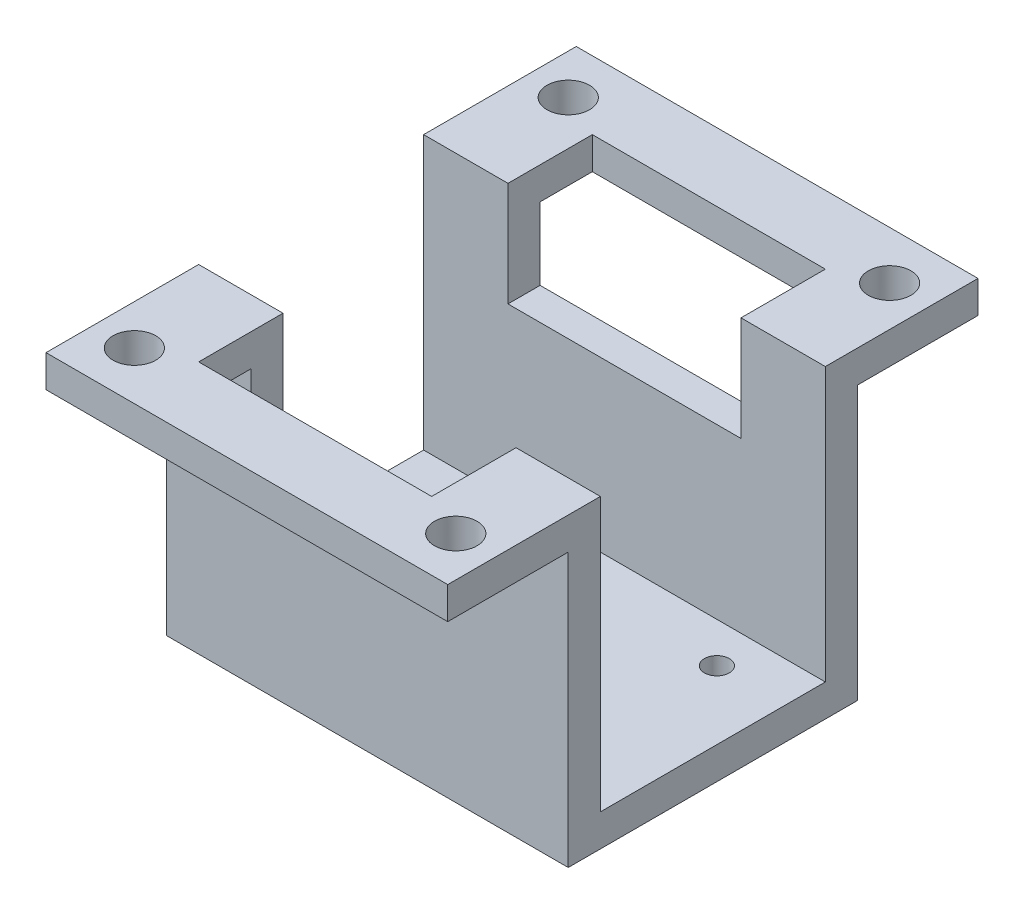
SolidWorks part; units mm, degrees
ref_plane "Front Plane" through (0, 0, 0) normal (0, 0, 1) x (1, 0, 0)
ref_plane "Top Plane" through (0, 0, 0) normal (0, 1, 0) x (1, 0, 0)
ref_plane "Right Plane" through (0, 0, 0) normal (1, 0, 0) x (0, 0, -1)
sketch "Sketch1" plane through (0, 0, 0) normal (0, 1, 0) x (1, 0, 0)
  line L6 (-8.5, 27) -> (41.5, 27)
  line L7 (-8.5, 27) -> (-8.5, -9)
  line L8 (-8.5, -9) -> (41.5, -9)
  line L9 (41.5, 27) -> (41.5, -9)
  circle A0 centre (0, 18) radius 1.55
  circle A1 centre (0, 0) radius 1.55
  circle A2 centre (33, 0) radius 1.55
  circle A3 centre (33, 18) radius 1.55
  circle A4 centre (9, 9) radius 8
  dimension "D3" = 3.1
  dimension "D8" = 16
  dimension "D1" = 33
  dimension "D2" = 18
  dimension "D4" = 50
  dimension "D5" = 36
extrude "Boss-Extrude1" add sketch "Sketch1" along normal blind 4
sketch "Sketch2" plane through (0, 4, 0) normal (0, 1, 0) x (1, 0, 0)
  line L0 (-8.5, -9) -> (41.5, -9)
  line L1 (-8.5, -5) -> (41.5, -5)
  line L2 (-8.5, -5) -> (-8.5, -9)
  line L3 (-8.5, -9) -> (-8.5964, -8.8741)
  line L4 (41.5, -5) -> (41.5, -9)
  line L5 (-8.5, 9) -> (41.5, 9) construction
  line L6 (-8.5, 27) -> (-8.5, -9) construction
  line L7 (41.5, -9) -> (41.5, 27) construction
  line L8 (-8.5, 23) -> (41.5, 23)
  line L9 (41.5, 23) -> (41.5, 27)
  line L10 (-8.5, 23) -> (-8.5, 27)
  line L11 (-8.5, 27) -> (41.5, 27)
  circle A0 centre (0, 0) radius 1.55
  circle A1 centre (0, 0) radius 2.75
  line M3 (41.5, -9) -> (41.5, 27)
  line M4 (41.5, 27) -> (-8.5, 27)
  line M5 (-8.5, 27) -> (-8.5, -9)
  line M6 (-8.5, -9) -> (41.5, -9)
  dimension "D1" = 5.5
  dimension "D2" = 4
extrude "Boss-Extrude3" add sketch "Sketch2" along normal blind 34 contours L1 M5 M6 M3 | L8 M5 M3 M4
sketch "Sketch3" plane through (0, 0, 9) normal (0, 0, 1) x (1, 0, 0)
  line L1 (2, 38) -> (31, 38)
  line L2 (2, 25) -> (31, 25)
  line L5 (2, 38) -> (2, 25)
  line L6 (31, 38) -> (31, 25)
extrude "Cut-Extrude1" cut sketch "Sketch3" against normal through all
sketch "Sketch6" plane through (0, 0, 9) normal (0, 0, 1) x (1, 0, 0)
  line L0 (31, 38) -> (41.5, 38)
  line L1 (-8.5, 38) -> (31, 38)
  line L2 (-8.5, 34) -> (2, 34)
  line L3 (2, 34) -> (41.5, 34)
  line L4 (-8.5, 38) -> (2, 38) construction
  line L5 (31, 34) -> (41.5, 34) construction
  line L6 (-8.5, 38) -> (-8.5, 34)
  line L7 (41.5, 38) -> (41.5, 34)
  dimension "D1" = 4
extrude "Boss-Extrude4" add sketch "Sketch6" along normal blind 15
sketch "Sketch7" plane through (0, 0, -27) normal (0, 0, -1) x (-1, 0, 0)
  line L0 (8.5, 38) -> (-41.5, 38)
  line L1 (8.5, 34) -> (-41.5, 34)
  line L2 (8.5, 38) -> (8.5, 34)
  line L3 (-41.5, 38) -> (-41.5, 34)
  dimension "D1" = 4
extrude "Boss-Extrude5" add sketch "Sketch7" along normal blind 15
sketch "Sketch9" plane through (0, 38, 0) normal (0, 1, 0) x (1, 0, 0)
  line L0 (2, 27) -> (31, 27)
  line L1 (2, -9) -> (31, -9)
  line L2 (2, 33.5) -> (31, 33.5)
  line L3 (2, -15.5) -> (31, -15.5)
  line L4 (2, 27) -> (2, 33.5)
  line L5 (31, 33.5) -> (31, 27)
  line L6 (2, -15.5) -> (2, -9)
  line L7 (31, -9) -> (31, -15.5)
  dimension "D1" = 6.5
  dimension "D2" = 6.5
extrude "Cut-Extrude2" cut sketch "Sketch9" against normal through all
sketch "Sketch10" plane through (0, 34, 0) normal (0, -1, 0) x (1, 0, 0)
  line L0 (41.5, -42) -> (36.5, -42)
  line L1 (16.5, -42) -> (16.5, 24) construction
  line L3 (-8.5, 24) -> (41.5, 24) construction
  line L4 (41.5, -42) -> (41.5, 24)
  line L5 (41.5, -42) -> (-8.5, -42) construction
  line L6 (41.5, -9) -> (-18.2111, -9) construction
  line L11 (36.25, -42) -> (38.9195, -42)
  line L12 (36.5, -42) -> (36.5, -36)
  circle A0 centre (36.5, -36) radius 2.65
  circle A1 centre (-3.5, -36) radius 2.65
  circle A2 centre (-3.5, 18) radius 2.65
  circle A3 centre (36.5, 18) radius 2.65
  dimension "D1" = 5.3
  dimension "D2" = 5
  dimension "D3" = 6
extrude "Cut-Extrude3" cut sketch "Sketch10" against normal through all
